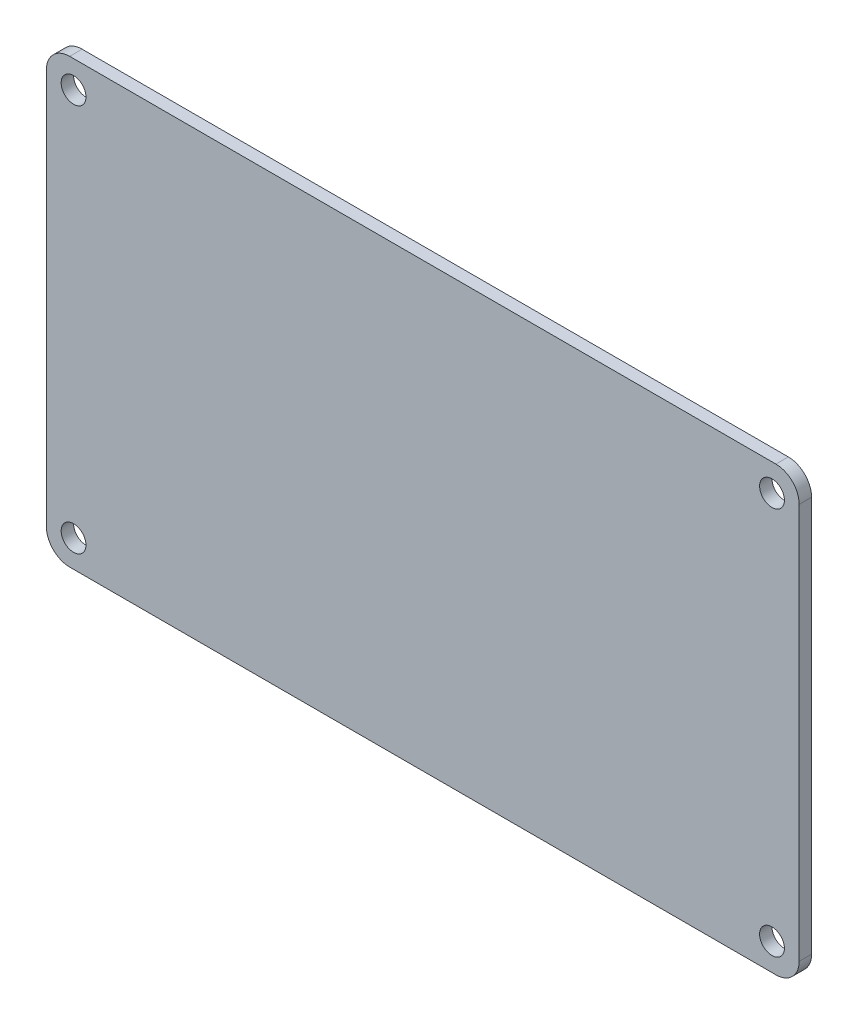
SolidWorks part; units mm, degrees
ref_plane "Front Plane" through (0, 0, 0) normal (0, 0, 1) x (1, 0, 0)
ref_plane "Top Plane" through (0, 0, 0) normal (0, 1, 0) x (1, 0, 0)
ref_plane "Right Plane" through (0, 0, 0) normal (1, 0, 0) x (0, 0, -1)
sketch "Sketch1" plane through (0, 0, 0) normal (0, 0, 1) x (1, 0, 0)
  line L1 (12.2689, 8.568) -> (103.2689, 8.568)
  line L2 (9.2689, 11.568) -> (9.2689, 62.568)
  line L3 (12.2689, 65.568) -> (103.2689, 65.568)
  line L4 (106.2689, 11.568) -> (106.2689, 62.568)
  arc A0 (103.2689, 8.568) -> (106.2689, 11.568) centre (103.2689, 11.568) ccw
  arc A1 (103.2689, 65.568) -> (106.2689, 62.568) centre (103.2689, 62.568) cw
  arc A2 (9.2689, 62.568) -> (12.2689, 65.568) centre (12.2689, 62.568) cw
  arc A3 (12.2689, 8.568) -> (9.2689, 11.568) centre (12.2689, 11.568) cw
  circle A4 centre (12.7689, 12.068) radius 1.6
  circle A5 centre (12.7689, 62.068) radius 1.6
  circle A6 centre (102.7689, 62.068) radius 1.6
  circle A7 centre (102.7689, 12.068) radius 1.6
  point P6 (106.2689, 8.568)
  point P11 (9.2689, 65.568)
  point P14 (9.2689, 8.568)
  point P15 (12.7689, 12.068)
  point P16 (12.7689, 62.068)
  point P17 (102.7689, 62.068)
  point P18 (102.7689, 12.068)
  dimension "D3" = 3
  dimension "D1" = 57
  dimension "D2" = 97
  dimension "D4" = 3.5
  dimension "D5" = 3.5
  dimension "D6" = 50
  dimension "D7" = 90
  dimension "D8" = 3.5
  dimension "D9" = 50
  dimension "D10" = 90
  dimension "D11" = 3.5
extrude "Boss-Extrude1" add sketch "Sketch1" along normal blind 1.6
